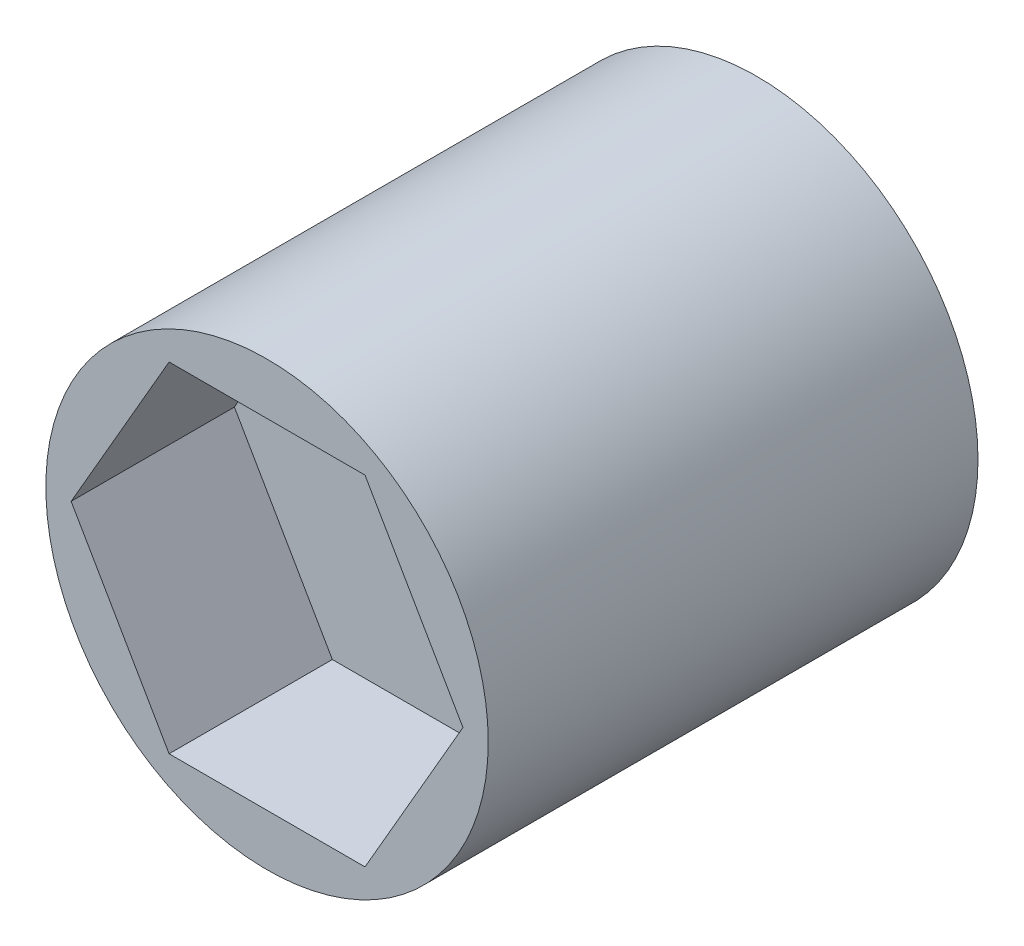
SolidWorks part; units mm, degrees
ref_plane "Front Plane" through (0, 0, 0) normal (0, 0, 1) x (1, 0, 0)
ref_plane "Top Plane" through (0, 0, 0) normal (0, 1, 0) x (1, 0, 0)
ref_plane "Right Plane" through (0, 0, 0) normal (1, 0, 0) x (0, 0, -1)
sketch "Sketch1" plane through (0, 0, 0) normal (0, 0, 1) x (1, 0, 0)
  circle A0 centre (0, 0) radius 6.775
  dimension "D1" = 13.55
extrude "Boss-Extrude1" add sketch "Sketch1" along normal blind 15
sketch "Sketch2" plane through (0, 0, 15) normal (0, 0, 1) x (1, 0, 0)
  line L1 (-3, -5.1962) -> (3, -5.1962)
  line L2 (3, -5.1962) -> (6, 0)
  line L3 (6, 0) -> (3, 5.1962)
  line L4 (3, 5.1962) -> (-3, 5.1962)
  line L5 (-3, 5.1962) -> (-6, 0)
  line L6 (-6, 0) -> (-3, -5.1962)
  circle A0 centre (0, 0) radius 5.1962 construction
  dimension "D1" = 6
extrude "Cut-Extrude1" cut sketch "Sketch2" against normal blind 5
